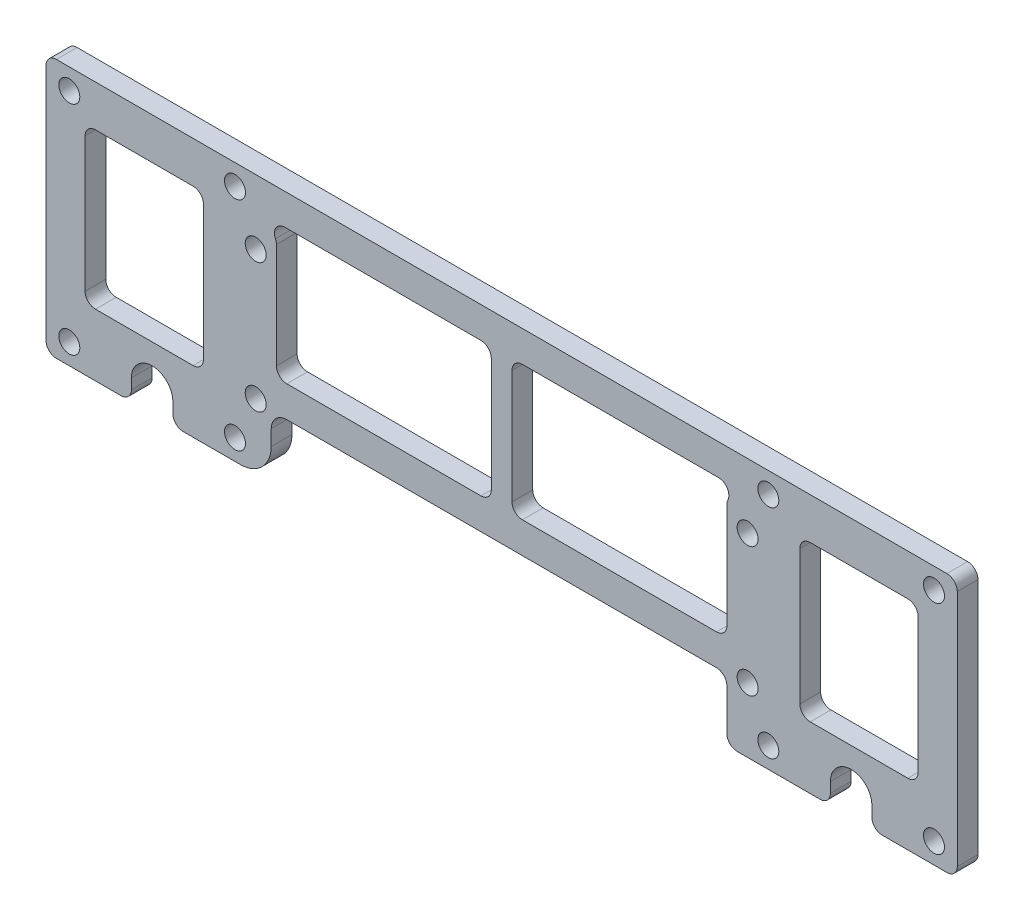
SolidWorks part; units mm, degrees
material "Thornel Mat VMA"
ref_plane "前视基准面" through (0, 0, 0) normal (0, 0, 1) x (1, 0, 0)
ref_plane "上视基准面" through (0, 0, 0) normal (0, 1, 0) x (1, 0, 0)
ref_plane "右视基准面" through (0, 0, 0) normal (1, 0, 0) x (0, 0, -1)
other "Configuration Table"
sketch "草图1" plane through (0, 0, 0) normal (0, 0, 1) x (1, 0, 0)
  line L1 (-88, -25) -> (88, -25)
  line L2 (-88, -25) -> (-88, 25)
  line L3 (-88, 25) -> (88, 25)
  line L4 (88, -25) -> (88, 25)
  line L5 (-88, -25) -> (88, 25) construction
  line L6 (-88, 25) -> (88, -25) construction
  point P0 (0, 0)
  dimension "D1" = 176
  dimension "D2" = 50
extrude "凸台-拉伸1" add sketch "草图1" along normal mid plane 4
sketch "草图2" plane through (0, 0, -2) normal (0, 0, -1) x (-1, 0, 0)
  line L0 (-88, -25) -> (-88, 25) construction
  line L1 (88, -25) -> (-88, -25) construction
  circle A4 centre (51.5, 21) radius 1.65 construction
  circle A5 centre (83.5, 21) radius 1.65 construction
  circle A6 centre (83.5, -21) radius 1.65 construction
  circle A7 centre (51.5, -21) radius 1.65 construction
  circle A8 centre (51.5, 21) radius 2.025
  circle A9 centre (51.5, -21) radius 2.025
  circle A10 centre (83.5, 21) radius 2.025
  circle A11 centre (83.5, -21) radius 2.025
  dimension "D1" = 4.05
  dimension "D2" = 3.3
  dimension "D3" = 139.5
  dimension "D4" = 171.5
  dimension "D5" = 4
  dimension "D6" = 46
extrude "切除-拉伸1" cut sketch "草图2" against normal mid plane 44
mirror "镜向1" about plane through (0, 0, 0) normal (1, 0, 0) of "切除-拉伸1"
sketch "草图3" plane through (0, 0, -2) normal (0, 0, -1) x (-1, 0, 0)
  line L0 (51.5, -21) -> (83.5, -21) construction
  line L1 (88, -25) -> (-88, -25) construction
  line L2 (67.5, -17) -> (64.0359, -19) construction
  line L3 (64.0359, -19) -> (64.0359, -23) construction
  line L4 (64.0359, -23) -> (67.5, -25) construction
  line L5 (67.5, -25) -> (70.9641, -23) construction
  line L6 (70.9641, -23) -> (70.9641, -19) construction
  line L7 (70.9641, -19) -> (67.5, -17) construction
  line L8 (63.5, -21) -> (63.5, -25)
  line L9 (63.5, -25) -> (71.5, -25)
  line L10 (71.5, -25) -> (71.5, -21)
  arc A1 (71.5, -21) -> (63.5, -21) centre (67.5, -21) ccw
extrude "切除-拉伸2" cut sketch "草图3" against normal mid plane 34
mirror "镜向2" about plane through (0, 0, 0) normal (1, 0, 0) of "切除-拉伸2"
fillet "圆角1" radius 2 8 edges at (-63.5, -25, 0) (-71.5, -25, 0) (-88, -25, 0) (-88, 25, 0) (88, 25, 0) (88, -25, 0) (63.5, -25, 0) (71.5, -25, 0)
sketch "草图4" plane through (0, 0, -2) normal (0, 0, -1) x (-1, 0, 0)
  line L0 (0, 0) -> (0, 39.7979) construction
  circle A0 centre (47.5, -12.5) radius 1.65 construction
  circle A1 centre (47.5, 12.5) radius 1.65 construction
  circle A2 centre (47.5, -12.5) radius 1.65 construction
  circle A3 centre (47.5, 12.5) radius 1.65 construction
  circle A4 centre (47.5, -12.5) radius 2.025
  circle A5 centre (47.5, 12.5) radius 2.025
  circle A7 centre (-47.5, 12.5) radius 1.65 construction
  circle A8 centre (-47.5, -12.5) radius 1.65 construction
  circle A9 centre (-47.5, 12.5) radius 2.025
  circle A10 centre (-47.5, -12.5) radius 2.025
  dimension "D1" = 4.05
extrude "切除-拉伸3" cut sketch "草图4" against normal mid plane 10
sketch "草图5" [suppressed] plane through (0, 0, -2) normal (0, 0, -1) x (-1, 0, 0)
  line L0 (61.5, -23) -> (-61.5, -23) construction
  line L1 (-47, -23) -> (47, -23)
  line L2 (-47, -23) -> (-47, -88)
  line L3 (-47, -88) -> (47, -88)
  line L4 (47, -23) -> (47, -88)
  line L5 (0, 0) -> (0, -88) construction
  dimension "D1" = 94
  dimension "D2" = 65
extrude "凸台-拉伸2" [suppressed] add sketch "草图5" against normal up to surface (4 mm away)
sketch "草图7" plane through (0, 0, 2) normal (0, 0, 1) x (1, 0, 0)
  line L5 (-45.0329, 19) -> (-43.5, 15.7427)
  line L6 (-43.5, 15.7427) -> (-43.5, -15.7427)
  line L7 (-43.5, -15.7427) -> (-45.0329, -19)
  line L8 (-45.0329, -19) -> (45.0329, -19)
  line L9 (0, -19) -> (0, 0) construction
  line L10 (-45.0329, 19) -> (45.0329, 19)
  line L11 (0, 0) -> (-43.5, 0) construction
  line L12 (-51.5, 21) -> (-47.5, 12.5) construction
  line L13 (-47.5, 12.5) -> (-47.5, -12.5) construction
  line L14 (-47.5, -12.5) -> (-51.5, -21) construction
  line L15 (-61.5, -25) -> (61.5, -25) construction
  line L16 (45.0329, 19) -> (43.5, 15.7427)
  line L17 (43.5, -15.7427) -> (45.0329, -19)
  line L18 (43.5, 15.7427) -> (43.5, -15.7427)
  line L19 (0, 19) -> (0, -19) construction
  line L20 (-2, 19) -> (-2, -19)
  line L21 (2, 19) -> (2, -19)
  point P23 (0, 19)
  dimension "D1" = 8
  dimension "D2" = 5
  dimension "D3" = 6
  dimension "D4" = 2
  dimension "D5" = 2
extrude "切除-拉伸5" cut sketch "草图7" against normal mid plane 31 contours L20 L10 L5 L6 L7 L8 | L10 L21 L8 L17 L18 L16
sketch "草图8" plane through (0, 0, 2) normal (0, 0, 1) x (1, 0, 0)
  line L0 (-83.5, 21) -> (-51.5, -21) construction
  line L1 (0, 0) -> (0, -25) construction
  line L2 (-80.4524, 17) -> (-57.5952, 17)
  line L3 (-80.4524, 17) -> (-80.4524, -13)
  line L4 (-80.4524, -13) -> (-57.5952, -13)
  line L5 (-57.5952, 17) -> (-57.5952, -13)
  line L6 (-61.5, -25) -> (61.5, -25) construction
  line L7 (80.4524, -13) -> (57.5952, -13)
  line L8 (57.5952, 17) -> (57.5952, -13)
  line L9 (80.4524, 17) -> (57.5952, 17)
  line L10 (80.4524, 17) -> (80.4524, -13)
  circle A0 centre (-51.5, 21) radius 2.025 construction
  arc A1 (-63.5, -21) -> (-71.5, -21) centre (-67.5, -21) ccw construction
  dimension "D1" = 4
  dimension "D2" = 8
extrude "切除-拉伸6" cut sketch "草图8" against normal mid plane 31
fillet "圆角2" radius 2 20 edges at (-45.0329, -19, 0) (-43.5, -15.7427, 0) (-43.5, 15.7427, 0) (-45.0329, 19, 0) (-2, 19, 0) (-2, -19, 0) (43.5, 15.7427, 0) (43.5, -15.7427, 0) (45.0329, -19, 0) (2, -19, 0) (2, 19, 0) (45.0329, 19, 0) (80.4524, -13, 0) (57.5952, -13, 0) (57.5952, 17, 0) (80.4524, 17, 0) (-80.4524, 17, 0) (-57.5952, 17, 0) (-80.4524, -13, 0) (-57.5952, -13, 0)
sketch "草图9" plane through (0, 0, -2) normal (0, 0, -1) x (-1, 0, 0)
  line L0 (0, -52) -> (0, 0) construction
  line L1 (65, -79) -> (-65, -79)
  line L2 (65, -79) -> (65, -25)
  line L3 (65, -25) -> (-65, -25)
  line L4 (-65, -79) -> (-65, -25)
  line L5 (65, -79) -> (-65, -25) construction
  line L6 (65, -25) -> (-65, -79) construction
  line L8 (61.5, -25) -> (-61.5, -25) construction
  point P0 (0, -52)
  dimension "D1" = 54
  dimension "D2" = 130
extrude "凸台-拉伸3" [suppressed] add sketch "草图9" against normal up to surface (4 mm away)
sketch "草图10" [suppressed] plane through (0, 0, -2) normal (0, 0, -1) x (-1, 0, 0)
  line L0 (-65, -79) -> (65, -79) construction
  line L1 (54.75, -26) -> (-54.75, -26)
  line L2 (54.75, -26) -> (54.75, -79)
  line L3 (54.75, -79) -> (-54.75, -79)
  line L4 (-54.75, -26) -> (-54.75, -79)
  line L5 (54.75, -26) -> (-54.75, -79) construction
  line L6 (54.75, -79) -> (-54.75, -26) construction
  line L7 (0, -52.5) -> (0, 0) construction
  point P0 (0, -52.5)
  dimension "D1" = 109.5
  dimension "D2" = 53
extrude "切除-拉伸7" [suppressed] cut sketch "草图10" against normal blind 10
sketch "草图11" [suppressed] plane through (0, 0, -2) normal (0, 0, -1) x (-1, 0, 0)
  line L1 (51.75, -26) -> (-51.75, -26)
  line L2 (51.75, -26) -> (51.75, -79)
  line L3 (51.75, -79) -> (-51.75, -79)
  line L4 (54.75, -26) -> (-54.75, -26)
  line L5 (-54.75, -26) -> (-54.75, -79)
  line L6 (-54.75, -79) -> (54.75, -79)
  line L7 (54.75, -79) -> (54.75, -26)
  line L8 (54.75, -26) -> (-54.75, -26)
  line L9 (-54.75, -26) -> (-54.75, -79)
  line L10 (-54.75, -79) -> (54.75, -79)
  line L11 (54.75, -79) -> (54.75, -26)
  line L12 (-51.75, -26) -> (-51.75, -79)
  line L13 (44.75, -26) -> (-44.75, -26)
  line L14 (44.75, -26) -> (44.75, -79)
  line L15 (44.75, -79) -> (-44.75, -79)
  line L16 (-44.75, -26) -> (-44.75, -79)
  dimension "D2" = 3
  dimension "D3" = 3
  dimension "D4" = 7
  dimension "D5" = 7
  dimension "D1" = 0
extrude "凸台-拉伸4" [suppressed] add sketch "草图11" against normal up to surface (4 mm away) contours L1 L14 L3 L2 | L16 L1 L12 L3
sketch "草图12" plane through (0, 0, -2) normal (0, 0, -1) x (-1, 0, 0)
  line L0 (-65, -25) -> (65, -25)
  line L2 (-51.75, -26) -> (-51.75, -25)
  line L3 (51.75, -26) -> (51.75, -25)
  line L13 (-61.5, -25) -> (61.5, -25)
  line L14 (-61.5, -25) -> (61.5, -25)
  line L44 (63.5, -23) -> (63.5, -21)
  line L45 (71.5, -21) -> (71.5, -23)
  line L46 (73.5, -25) -> (86, -25)
  line L47 (88, -23) -> (88, 23)
  line L48 (86, 25) -> (-86, 25)
  line L49 (-88, 23) -> (-88, -23)
  line L50 (-86, -25) -> (-73.5, -25)
  line L51 (-71.5, -23) -> (-71.5, -21)
  line L52 (-63.5, -21) -> (-63.5, -23)
  line L70 (63.5, -23) -> (63.5, -21)
  line L71 (71.5, -21) -> (71.5, -23)
  line L72 (73.5, -25) -> (86, -25)
  line L73 (88, -23) -> (88, 23)
  line L74 (86, 25) -> (-86, 25)
  line L75 (-88, 23) -> (-88, -23)
  line L76 (-86, -25) -> (-73.5, -25)
  line L77 (-71.5, -23) -> (-71.5, -21)
  line L78 (-63.5, -21) -> (-63.5, -23)
  arc A10 (61.5, -25) -> (63.5, -23) centre (61.5, -23) ccw
  arc A11 (71.5, -21) -> (63.5, -21) centre (67.5, -21) ccw
  arc A12 (71.5, -23) -> (73.5, -25) centre (73.5, -23) ccw
  arc A13 (86, -25) -> (88, -23) centre (86, -23) ccw
  arc A14 (88, 23) -> (86, 25) centre (86, 23) ccw
  arc A15 (-86, 25) -> (-88, 23) centre (-86, 23) ccw
  arc A16 (-88, -23) -> (-86, -25) centre (-86, -23) ccw
  arc A17 (-73.5, -25) -> (-71.5, -23) centre (-73.5, -23) ccw
  arc A18 (-63.5, -21) -> (-71.5, -21) centre (-67.5, -21) ccw
  arc A19 (-63.5, -23) -> (-61.5, -25) centre (-61.5, -23) ccw
  arc A20 (61.5, -25) -> (63.5, -23) centre (61.5, -23) ccw
  arc A21 (71.5, -21) -> (63.5, -21) centre (67.5, -21) ccw
  arc A22 (71.5, -23) -> (73.5, -25) centre (73.5, -23) ccw
  arc A23 (86, -25) -> (88, -23) centre (86, -23) ccw
  arc A24 (88, 23) -> (86, 25) centre (86, 23) ccw
  arc A25 (-86, 25) -> (-88, 23) centre (-86, 23) ccw
  arc A26 (-88, -23) -> (-86, -25) centre (-86, -23) ccw
  arc A27 (-73.5, -25) -> (-71.5, -23) centre (-73.5, -23) ccw
  arc A28 (-63.5, -21) -> (-71.5, -21) centre (-67.5, -21) ccw
  arc A29 (-63.5, -23) -> (-61.5, -25) centre (-61.5, -23) ccw
  dimension "D1" = 0
extrude "切除-拉伸8" [suppressed] cut sketch "草图12" against normal blind 10
sketch "草图13" plane through (0, 0, 2) normal (0, 0, 1) x (1, 0, 0)
  line L0 (0, -54) -> (0, 0) construction
  line L1 (-48.75, -44) -> (48.75, -44) construction
  line L2 (-48.75, -44) -> (-48.75, -64) construction
  line L3 (-48.75, -64) -> (48.75, -64) construction
  line L4 (48.75, -44) -> (48.75, -64) construction
  line L5 (-48.75, -44) -> (48.75, -64) construction
  line L6 (-48.75, -64) -> (48.75, -44) construction
  circle A2 centre (-48.75, -44) radius 1.51
  circle A3 centre (-48.75, -64) radius 1.51
  circle A4 centre (48.75, -44) radius 1.51
  circle A5 centre (48.75, -64) radius 1.51
  point P0 (0, -54)
  dimension "D4" = 3.02
  dimension "D1" = 97.5
  dimension "D2" = 20
  dimension "D3" = 44
extrude "切除-拉伸9" [suppressed] cut sketch "草图13" against normal blind 10
fillet "圆角3" [suppressed] radius 15
sketch "草图14" [suppressed] plane through (0, 0, -2) normal (0, 0, -1) x (-1, 0, 0)
  line L4 (-80.4524, 15) -> (-80.4524, -11)
  line L5 (-59.5952, 17) -> (-78.4524, 17)
  line L6 (-43.5, 15.2956) -> (-43.5, -15.2956)
  line L7 (-43.6909, 16.1484) -> (-43.6904, 16.1472)
  line L8 (-4, 19) -> (-41.8813, 19)
  line L9 (-2, -17) -> (-2, 17)
  line L10 (-41.8813, -19) -> (-4, -19)
  line L11 (-43.6904, -16.1472) -> (-43.6909, -16.1484)
  line L12 (-43.5, 15.2956) -> (-43.5, -15.2956)
  line L13 (-43.6909, 16.1484) -> (-43.6904, 16.1472)
  line L14 (-4, 19) -> (-41.8813, 19)
  line L15 (-2, -17) -> (-2, 17)
  line L16 (-41.8813, -19) -> (-4, -19)
  line L17 (-43.6904, -16.1472) -> (-43.6909, -16.1484)
  line L18 (43.5, -15.2956) -> (43.5, 15.2956)
  line L19 (43.6909, -16.1484) -> (43.6904, -16.1472)
  line L20 (4, -19) -> (41.8813, -19)
  line L21 (2, 17) -> (2, -17)
  line L22 (41.8813, 19) -> (4, 19)
  line L23 (43.6904, 16.1472) -> (43.6909, 16.1484)
  line L24 (43.5, -15.2956) -> (43.5, 15.2956)
  line L25 (43.6909, -16.1484) -> (43.6904, -16.1472)
  line L26 (4, -19) -> (41.8813, -19)
  line L27 (2, 17) -> (2, -17)
  line L28 (41.8813, 19) -> (4, 19)
  line L29 (43.6904, 16.1472) -> (43.6909, 16.1484)
  line L30 (-57.5952, -11) -> (-57.5952, 15)
  line L31 (-78.4524, -13) -> (-59.5952, -13)
  line L32 (-80.4524, 15) -> (-80.4524, -11)
  line L33 (-59.5952, 17) -> (-78.4524, 17)
  line L34 (-57.5952, -11) -> (-57.5952, 15)
  line L35 (-78.4524, -13) -> (-59.5952, -13)
  line L36 (80.4524, -11) -> (80.4524, 15)
  line L37 (59.5952, -13) -> (78.4524, -13)
  line L38 (57.5952, 15) -> (57.5952, -11)
  line L39 (78.4524, 17) -> (59.5952, 17)
  line L40 (80.4524, -11) -> (80.4524, 15)
  line L41 (59.5952, -13) -> (78.4524, -13)
  line L42 (57.5952, 15) -> (57.5952, -11)
  line L43 (78.4524, 17) -> (59.5952, 17)
  circle A1 centre (51.5, 21) radius 2.025
  circle A2 centre (51.5, 21) radius 2.025
  circle A3 centre (83.5, -21) radius 2.025
  circle A4 centre (83.5, -21) radius 2.025
  circle A5 centre (83.5, 21) radius 2.025
  circle A6 centre (83.5, 21) radius 2.025
  circle A7 centre (51.5, -21) radius 2.025
  circle A8 centre (51.5, -21) radius 2.025
  circle A9 centre (-51.5, 21) radius 2.025
  circle A10 centre (-51.5, 21) radius 2.025
  circle A11 centre (-83.5, -21) radius 2.025
  circle A12 centre (-83.5, -21) radius 2.025
  circle A13 centre (-83.5, 21) radius 2.025
  circle A14 centre (-83.5, 21) radius 2.025
  circle A15 centre (-51.5, -21) radius 2.025
  circle A16 centre (-51.5, -21) radius 2.025
  circle A17 centre (47.5, -12.5) radius 2.025
  circle A18 centre (47.5, -12.5) radius 2.025
  circle A19 centre (47.5, 12.5) radius 2.025
  circle A20 centre (47.5, 12.5) radius 2.025
  circle A21 centre (-47.5, 12.5) radius 2.025
  circle A22 centre (-47.5, 12.5) radius 2.025
  circle A23 centre (-47.5, -12.5) radius 2.025
  circle A24 centre (-47.5, -12.5) radius 2.025
  circle A25 centre (48.75, -44) radius 1.51
  circle A26 centre (48.75, -44) radius 1.51
  circle A27 centre (-48.75, -64) radius 1.51
  arc A28 (-78.4524, 17) -> (-80.4524, 15) centre (-78.4524, 15) ccw
  arc A29 (-57.5952, 15) -> (-59.5952, 17) centre (-59.5952, 15) ccw
  arc A30 (-43.5, 15.2956) -> (-43.6904, 16.1472) centre (-45.5, 15.2956) ccw
  arc A31 (-41.8813, 19) -> (-43.6909, 16.1484) centre (-41.8813, 17) ccw
  arc A32 (-2, 17) -> (-4, 19) centre (-4, 17) ccw
  arc A33 (-4, -19) -> (-2, -17) centre (-4, -17) ccw
  arc A34 (-43.6909, -16.1484) -> (-41.8813, -19) centre (-41.8813, -17) ccw
  arc A35 (-43.6904, -16.1472) -> (-43.5, -15.2956) centre (-45.5, -15.2956) ccw
  arc A36 (-43.5, 15.2956) -> (-43.6904, 16.1472) centre (-45.5, 15.2956) ccw
  arc A37 (-41.8813, 19) -> (-43.6909, 16.1484) centre (-41.8813, 17) ccw
  arc A38 (-2, 17) -> (-4, 19) centre (-4, 17) ccw
  arc A39 (-4, -19) -> (-2, -17) centre (-4, -17) ccw
  arc A40 (-43.6909, -16.1484) -> (-41.8813, -19) centre (-41.8813, -17) ccw
  arc A41 (-43.6904, -16.1472) -> (-43.5, -15.2956) centre (-45.5, -15.2956) ccw
  arc A42 (43.5, -15.2956) -> (43.6904, -16.1472) centre (45.5, -15.2956) ccw
  arc A43 (41.8813, -19) -> (43.6909, -16.1484) centre (41.8813, -17) ccw
  arc A44 (2, -17) -> (4, -19) centre (4, -17) ccw
  arc A45 (4, 19) -> (2, 17) centre (4, 17) ccw
  arc A46 (43.6909, 16.1484) -> (41.8813, 19) centre (41.8813, 17) ccw
  arc A47 (43.6904, 16.1472) -> (43.5, 15.2956) centre (45.5, 15.2956) ccw
  arc A48 (43.5, -15.2956) -> (43.6904, -16.1472) centre (45.5, -15.2956) ccw
  arc A49 (41.8813, -19) -> (43.6909, -16.1484) centre (41.8813, -17) ccw
  arc A50 (2, -17) -> (4, -19) centre (4, -17) ccw
  arc A51 (4, 19) -> (2, 17) centre (4, 17) ccw
  arc A52 (43.6909, 16.1484) -> (41.8813, 19) centre (41.8813, 17) ccw
  arc A53 (43.6904, 16.1472) -> (43.5, 15.2956) centre (45.5, 15.2956) ccw
  arc A54 (-59.5952, -13) -> (-57.5952, -11) centre (-59.5952, -11) ccw
  arc A55 (-80.4524, -11) -> (-78.4524, -13) centre (-78.4524, -11) ccw
  arc A56 (-78.4524, 17) -> (-80.4524, 15) centre (-78.4524, 15) ccw
  arc A57 (-57.5952, 15) -> (-59.5952, 17) centre (-59.5952, 15) ccw
  arc A58 (-59.5952, -13) -> (-57.5952, -11) centre (-59.5952, -11) ccw
  arc A59 (-80.4524, -11) -> (-78.4524, -13) centre (-78.4524, -11) ccw
  arc A60 (78.4524, -13) -> (80.4524, -11) centre (78.4524, -11) ccw
  arc A61 (57.5952, -11) -> (59.5952, -13) centre (59.5952, -11) ccw
  arc A62 (59.5952, 17) -> (57.5952, 15) centre (59.5952, 15) ccw
  arc A63 (80.4524, 15) -> (78.4524, 17) centre (78.4524, 15) ccw
  arc A64 (78.4524, -13) -> (80.4524, -11) centre (78.4524, -11) ccw
  arc A65 (57.5952, -11) -> (59.5952, -13) centre (59.5952, -11) ccw
  arc A66 (59.5952, 17) -> (57.5952, 15) centre (59.5952, 15) ccw
  arc A67 (80.4524, 15) -> (78.4524, 17) centre (78.4524, 15) ccw
  circle A68 centre (-48.75, -64) radius 1.51
  circle A69 centre (-48.75, -44) radius 1.51
  circle A70 centre (-48.75, -44) radius 1.51
  circle A71 centre (48.75, -64) radius 1.51
  circle A72 centre (48.75, -64) radius 1.51
  dimension "D1" = 0
  dimension "D2" = 0
  dimension "D3" = 0
  dimension "D4" = 0
  dimension "D5" = 0
  dimension "D6" = 0
  dimension "D7" = 0
  dimension "D8" = 0
  dimension "D9" = 0
  dimension "D10" = 0
  dimension "D11" = 0
  dimension "D12" = 0
  dimension "D13" = 0
  dimension "D14" = 0
  dimension "D15" = 0
  dimension "D16" = 0
  dimension "D17" = 0
  dimension "D18" = 0
  dimension "D19" = 0
  dimension "D20" = 0
other "移动面2" [suppressed] parameters "D1"=1
sketch "草图15" [suppressed] plane through (0, 0, -2) normal (0, 0, -1) x (-1, 0, 0)
  line L0 (45.75, -26) -> (43.8413, -16.6019)
  line L1 (-44.75, -26) -> (-43.8722, -16.8098)
  line L2 (-44.75, -26) -> (45.75, -26)
  line L3 (4, 19) -> (-4, 19)
  line L4 (-80.4524, 15) -> (-80.4524, -11)
  line L5 (-59.5952, 17) -> (-78.4524, 17)
  line L6 (-43.5, 15.2956) -> (-43.5, -15.2956)
  line L7 (-43.6909, 16.1484) -> (-43.6904, 16.1472)
  line L8 (-4, 19) -> (-41.8813, 19)
  line L9 (-2, -17) -> (-2, 17)
  line L10 (-41.8813, -19) -> (-4, -19)
  line L11 (-43.6904, -16.1472) -> (-43.6909, -16.1484)
  line L12 (-43.5, 15.2956) -> (-43.5, -15.2956)
  line L13 (-43.6909, 16.1484) -> (-43.6904, 16.1472)
  line L14 (-4, 19) -> (-41.8813, 19)
  line L15 (-2, -17) -> (-2, 17)
  line L16 (-41.8813, -19) -> (-4, -19)
  line L17 (-43.6904, -16.1472) -> (-43.6909, -16.1484)
  line L18 (43.5, -15.2956) -> (43.5, 15.2956)
  line L19 (43.6909, -16.1484) -> (43.6904, -16.1472)
  line L20 (4, -19) -> (41.8813, -19)
  line L21 (2, 17) -> (2, -17)
  line L22 (41.8813, 19) -> (4, 19)
  line L23 (43.6904, 16.1472) -> (43.6909, 16.1484)
  line L24 (43.5, -15.2956) -> (43.5, 15.2956)
  line L25 (43.6909, -16.1484) -> (43.6904, -16.1472)
  line L26 (4, -19) -> (41.8813, -19)
  line L27 (2, 17) -> (2, -17)
  line L28 (41.8813, 19) -> (4, 19)
  line L29 (43.6904, 16.1472) -> (43.6909, 16.1484)
  line L30 (-57.5952, -11) -> (-57.5952, 15)
  line L31 (-78.4524, -13) -> (-59.5952, -13)
  line L32 (-80.4524, 15) -> (-80.4524, -11)
  line L33 (-59.5952, 17) -> (-78.4524, 17)
  line L34 (-57.5952, -11) -> (-57.5952, 15)
  line L35 (-78.4524, -13) -> (-59.5952, -13)
  line L36 (80.4524, -11) -> (80.4524, 15)
  line L37 (59.5952, -13) -> (78.4524, -13)
  line L38 (57.5952, 15) -> (57.5952, -11)
  line L39 (78.4524, 17) -> (59.5952, 17)
  line L40 (80.4524, -11) -> (80.4524, 15)
  line L41 (59.5952, -13) -> (78.4524, -13)
  line L42 (57.5952, 15) -> (57.5952, -11)
  line L43 (78.4524, 17) -> (59.5952, 17)
  line L44 (-44.75, -79) -> (-40.75, -79)
  line L45 (-40.75, -79) -> (-40.75, -39)
  line L46 (-40.75, -39) -> (-20.75, -26)
  line L60 (51.75, -79) -> (51.75, -25)
  line L61 (63.5, -23) -> (63.5, -21)
  line L62 (71.5, -21) -> (71.5, -23)
  line L63 (73.5, -25) -> (86, -25)
  line L64 (88, -23) -> (88, 23)
  line L65 (86, 25) -> (-86, 25)
  line L66 (-88, 23) -> (-88, -23)
  line L67 (-86, -25) -> (-73.5, -25)
  line L68 (-71.5, -23) -> (-71.5, -21)
  line L69 (-63.5, -21) -> (-63.5, -23)
  line L70 (-51.75, -25) -> (-51.75, -79)
  line L71 (-51.75, -79) -> (-44.75, -79)
  line L72 (-44.75, -79) -> (-44.75, -26)
  line L73 (-44.75, -26) -> (44.75, -26)
  line L74 (44.75, -26) -> (44.75, -79)
  line L75 (44.75, -79) -> (51.75, -79)
  line L76 (51.75, -79) -> (51.75, -25)
  line L77 (63.5, -23) -> (63.5, -21)
  line L78 (71.5, -21) -> (71.5, -23)
  line L79 (73.5, -25) -> (86, -25)
  line L80 (88, -23) -> (88, 23)
  line L81 (86, 25) -> (-86, 25)
  line L82 (-88, 23) -> (-88, -23)
  line L83 (-86, -25) -> (-73.5, -25)
  line L84 (-71.5, -23) -> (-71.5, -21)
  line L85 (-63.5, -21) -> (-63.5, -23)
  line L86 (-51.75, -25) -> (-51.75, -79)
  line L87 (-51.75, -79) -> (-44.75, -79)
  line L88 (-44.75, -79) -> (-44.75, -26)
  line L89 (-44.75, -26) -> (44.75, -26)
  line L90 (44.75, -26) -> (44.75, -79)
  line L91 (44.75, -79) -> (51.75, -79)
  line L97 (51.75, -25) -> (61.5, -25)
  line L98 (51.75, -25) -> (61.5, -25)
  line L99 (-61.5, -25) -> (-51.75, -25)
  line L100 (-61.5, -25) -> (-51.75, -25)
  arc A0 (41.8813, -19) -> (43.6909, -16.1484) centre (41.8813, -17) ccw construction
  circle A1 centre (51.5, 21) radius 2.025
  circle A2 centre (51.5, 21) radius 2.025
  circle A3 centre (83.5, -21) radius 2.025
  circle A4 centre (83.5, -21) radius 2.025
  circle A5 centre (83.5, 21) radius 2.025
  circle A6 centre (83.5, 21) radius 2.025
  circle A7 centre (51.5, -21) radius 2.025
  circle A8 centre (51.5, -21) radius 2.025
  circle A9 centre (-51.5, 21) radius 2.025
  circle A10 centre (-51.5, 21) radius 2.025
  circle A11 centre (-83.5, -21) radius 2.025
  circle A12 centre (-83.5, -21) radius 2.025
  circle A13 centre (-83.5, 21) radius 2.025
  circle A14 centre (-83.5, 21) radius 2.025
  circle A15 centre (-51.5, -21) radius 2.025
  circle A16 centre (-51.5, -21) radius 2.025
  circle A17 centre (47.5, -12.5) radius 2.025
  circle A18 centre (47.5, -12.5) radius 2.025
  circle A19 centre (47.5, 12.5) radius 2.025
  circle A20 centre (47.5, 12.5) radius 2.025
  circle A21 centre (-47.5, 12.5) radius 2.025
  circle A22 centre (-47.5, 12.5) radius 2.025
  circle A23 centre (-47.5, -12.5) radius 2.025
  circle A24 centre (-47.5, -12.5) radius 2.025
  circle A25 centre (48.75, -44) radius 1.51
  circle A26 centre (48.75, -44) radius 1.51
  circle A27 centre (-48.75, -64) radius 1.51
  arc A28 (-78.4524, 17) -> (-80.4524, 15) centre (-78.4524, 15) ccw
  arc A29 (-57.5952, 15) -> (-59.5952, 17) centre (-59.5952, 15) ccw
  arc A30 (-43.5, 15.2956) -> (-43.6904, 16.1472) centre (-45.5, 15.2956) ccw
  arc A31 (-41.8813, 19) -> (-43.6909, 16.1484) centre (-41.8813, 17) ccw
  arc A32 (-2, 17) -> (-4, 19) centre (-4, 17) ccw
  arc A33 (-4, -19) -> (-2, -17) centre (-4, -17) ccw
  arc A34 (-43.6909, -16.1484) -> (-41.8813, -19) centre (-41.8813, -17) ccw
  arc A35 (-43.6904, -16.1472) -> (-43.5, -15.2956) centre (-45.5, -15.2956) ccw
  arc A36 (-43.5, 15.2956) -> (-43.6904, 16.1472) centre (-45.5, 15.2956) ccw
  arc A37 (-41.8813, 19) -> (-43.6909, 16.1484) centre (-41.8813, 17) ccw
  arc A38 (-2, 17) -> (-4, 19) centre (-4, 17) ccw
  arc A39 (-4, -19) -> (-2, -17) centre (-4, -17) ccw
  arc A40 (-43.6909, -16.1484) -> (-41.8813, -19) centre (-41.8813, -17) ccw
  arc A41 (-43.6904, -16.1472) -> (-43.5, -15.2956) centre (-45.5, -15.2956) ccw
  arc A42 (43.5, -15.2956) -> (43.6904, -16.1472) centre (45.5, -15.2956) ccw
  arc A43 (41.8813, -19) -> (43.6909, -16.1484) centre (41.8813, -17) ccw
  arc A44 (2, -17) -> (4, -19) centre (4, -17) ccw
  arc A45 (4, 19) -> (2, 17) centre (4, 17) ccw
  arc A46 (43.6909, 16.1484) -> (41.8813, 19) centre (41.8813, 17) ccw
  arc A47 (43.6904, 16.1472) -> (43.5, 15.2956) centre (45.5, 15.2956) ccw
  arc A48 (43.5, -15.2956) -> (43.6904, -16.1472) centre (45.5, -15.2956) ccw
  arc A49 (41.8813, -19) -> (43.6909, -16.1484) centre (41.8813, -17) ccw
  arc A50 (2, -17) -> (4, -19) centre (4, -17) ccw
  arc A51 (4, 19) -> (2, 17) centre (4, 17) ccw
  arc A52 (43.6909, 16.1484) -> (41.8813, 19) centre (41.8813, 17) ccw
  arc A53 (43.6904, 16.1472) -> (43.5, 15.2956) centre (45.5, 15.2956) ccw
  arc A54 (-59.5952, -13) -> (-57.5952, -11) centre (-59.5952, -11) ccw
  arc A55 (-80.4524, -11) -> (-78.4524, -13) centre (-78.4524, -11) ccw
  arc A56 (-78.4524, 17) -> (-80.4524, 15) centre (-78.4524, 15) ccw
  arc A57 (-57.5952, 15) -> (-59.5952, 17) centre (-59.5952, 15) ccw
  arc A58 (-59.5952, -13) -> (-57.5952, -11) centre (-59.5952, -11) ccw
  arc A59 (-80.4524, -11) -> (-78.4524, -13) centre (-78.4524, -11) ccw
  arc A60 (78.4524, -13) -> (80.4524, -11) centre (78.4524, -11) ccw
  arc A61 (57.5952, -11) -> (59.5952, -13) centre (59.5952, -11) ccw
  arc A62 (59.5952, 17) -> (57.5952, 15) centre (59.5952, 15) ccw
  arc A63 (80.4524, 15) -> (78.4524, 17) centre (78.4524, 15) ccw
  arc A64 (78.4524, -13) -> (80.4524, -11) centre (78.4524, -11) ccw
  arc A65 (57.5952, -11) -> (59.5952, -13) centre (59.5952, -11) ccw
  arc A66 (59.5952, 17) -> (57.5952, 15) centre (59.5952, 15) ccw
  arc A67 (80.4524, 15) -> (78.4524, 17) centre (78.4524, 15) ccw
  circle A68 centre (-48.75, -64) radius 1.51
  circle A69 centre (-48.75, -44) radius 1.51
  circle A70 centre (-48.75, -44) radius 1.51
  circle A71 centre (48.75, -64) radius 1.51
  circle A72 centre (48.75, -64) radius 1.51
  arc A87 (61.5, -25) -> (63.5, -23) centre (61.5, -23) ccw
  arc A88 (71.5, -21) -> (63.5, -21) centre (67.5, -21) ccw
  arc A89 (71.5, -23) -> (73.5, -25) centre (73.5, -23) ccw
  arc A90 (86, -25) -> (88, -23) centre (86, -23) ccw
  arc A91 (88, 23) -> (86, 25) centre (86, 23) ccw
  arc A92 (-86, 25) -> (-88, 23) centre (-86, 23) ccw
  arc A93 (-88, -23) -> (-86, -25) centre (-86, -23) ccw
  arc A94 (-73.5, -25) -> (-71.5, -23) centre (-73.5, -23) ccw
  arc A95 (-63.5, -21) -> (-71.5, -21) centre (-67.5, -21) ccw
  arc A96 (-63.5, -23) -> (-61.5, -25) centre (-61.5, -23) ccw
  arc A99 (61.5, -25) -> (63.5, -23) centre (61.5, -23) ccw
  arc A100 (71.5, -21) -> (63.5, -21) centre (67.5, -21) ccw
  arc A101 (71.5, -23) -> (73.5, -25) centre (73.5, -23) ccw
  arc A102 (86, -25) -> (88, -23) centre (86, -23) ccw
  arc A103 (88, 23) -> (86, 25) centre (86, 23) ccw
  arc A104 (-86, 25) -> (-88, 23) centre (-86, 23) ccw
  arc A105 (-88, -23) -> (-86, -25) centre (-86, -23) ccw
  arc A106 (-73.5, -25) -> (-71.5, -23) centre (-73.5, -23) ccw
  arc A107 (-63.5, -21) -> (-71.5, -21) centre (-67.5, -21) ccw
  arc A108 (-63.5, -23) -> (-61.5, -25) centre (-61.5, -23) ccw
  dimension "D22" = 4
  dimension "D23" = 13
  dimension "D24" = 20
  dimension "D1" = 0
  dimension "D2" = 0
  dimension "D3" = 0
  dimension "D4" = 0
  dimension "D5" = 0
  dimension "D6" = 0
  dimension "D7" = 0
  dimension "D8" = 0
  dimension "D9" = 0
  dimension "D10" = 0
  dimension "D11" = 0
  dimension "D12" = 0
  dimension "D13" = 0
  dimension "D14" = 0
  dimension "D15" = 0
  dimension "D16" = 0
  dimension "D17" = 0
  dimension "D18" = 0
  dimension "D19" = 0
  dimension "D20" = 0
  dimension "D21" = 0
extrude "凸台-拉伸5" [suppressed] add sketch "草图15" against normal up to surface (4 mm away) contours L88 L44 L45 L46 L2
sketch "草图16" [suppressed] plane through (0, 0, 2) normal (0, 0, 1) x (1, 0, 0)
  line L0 (-20.75, -26) -> (-8.75, -14)
  line L1 (-8.75, -14) -> (8.75, -14)
  line L2 (8.75, -14) -> (20.75, -26)
  line L3 (20.75, -26) -> (40.75, -39) construction
  line L4 (-45.75, -26) -> (20.75, -26) construction
  line L5 (0, 0) -> (0, -22.2739) construction
  line L6 (-20.75, -26) -> (20.75, -26)
  dimension "D1" = 45
  dimension "D2" = 14
extrude "切除-拉伸11" [suppressed] cut sketch "草图16" against normal blind 10
sketch "草图17" [suppressed] plane through (0, 0, -2) normal (0, 0, -1) x (-1, 0, 0)
  line L0 (30.4069, -30) -> (10.4069, -10)
  line L1 (10.4069, -10) -> (-10.4069, -10)
  line L2 (-10.4069, -10) -> (-30.4069, -30)
  line L3 (-30.4069, -30) -> (30.4069, -30)
  line L4 (20.75, -26) -> (8.75, -14)
  line L5 (8.75, -14) -> (-8.75, -14)
  line L6 (-8.75, -14) -> (-20.75, -26)
  line L7 (-20.75, -26) -> (20.75, -26)
  line L8 (20.75, -26) -> (8.75, -14)
  line L9 (8.75, -14) -> (-8.75, -14)
  line L10 (-8.75, -14) -> (-20.75, -26)
  line L11 (-20.75, -26) -> (20.75, -26)
  line L12 (-17, -16.5931) -> (-17, 19)
  line L13 (-41.8813, 19) -> (-4, 19) construction
  line L14 (45.75, -37) -> (30.4069, -30)
  line L15 (26.4069, -26) -> (45.75, -26)
  line L16 (45.75, -26) -> (45.75, -37)
  line L17 (45.75, -26) -> (45.75, -79) construction
  line L18 (17, -16.5931) -> (17, 19)
  line L19 (4, 19) -> (41.8813, 19) construction
  line L20 (17, -4) -> (32, -19)
  line L21 (13.75, -19) -> (41.8813, -19) construction
  line L22 (19.4069, -19) -> (32, -19)
  line L23 (-13.75, -19) -> (-19.4069, -19)
  line L24 (19.4069, -19) -> (13.75, -19)
  line L25 (-17, 19) -> (17, 19)
  line L26 (-17, -4) -> (-32, -19)
  line L27 (-32, -19) -> (-19.4069, -19)
  dimension "D3" = 11
  dimension "D4" = 45
  dimension "D5" = 32
  dimension "D6" = 17
  dimension "D7" = 17
  dimension "D8" = 45
  dimension "D1" = 0
  dimension "D2" = 4
extrude "凸台-拉伸6" [suppressed] add sketch "草图17" against normal up to surface (4 mm away) contours L24 L0 L1 L2 L23 L10 L9 L8 | L25 L12 L2 L1 L0 L18 | L0 L22 L20 L18 | L16 L15 L0 L14 | L26 L27 L2 L12
fillet "圆角4" [suppressed] radius 15
fillet "圆角5" [suppressed] radius 7
sketch "草图18" [suppressed] plane through (0, 0, 2) normal (0, 0, 1) x (1, 0, 0)
  line L0 (-30.4069, -30) -> (-20.0038, -25.2538)
  line L1 (-20.0038, -25.2538) -> (-20.75, -26)
  line L2 (-20.75, -26) -> (-26.4069, -26)
  line L3 (-26.4069, -26) -> (-30.4069, -30)
  line L7 (-8.75, -14) -> (-20.75, -26) construction
  line L8 (-30.4069, -30) -> (-41.6555, -35.132) construction
extrude "凸台-拉伸7" [suppressed] add sketch "草图18" against normal up to surface (4 mm away) contours L2 L3 L0
sketch "草图19" [suppressed] plane through (0, 0, 2) normal (0, 0, 1) x (1, 0, 0)
  line L0 (-21.6393, -26) -> (-20.75, -26)
  line L1 (-20.75, -26) -> (-20.0038, -25.2538)
  line L2 (-20.0038, -25.2538) -> (-21.6393, -26)
  line L3 (-30.4069, -30) -> (-41.6555, -35.132) construction
  line L4 (-8.75, -14) -> (-20.75, -26) construction
extrude "切除-拉伸12" [suppressed] cut sketch "草图19" against normal blind 10 contours L2 L0 L1
fillet "圆角6" [suppressed] radius 20
fillet "圆角7" [suppressed] radius 8
sketch "草图21" [suppressed] plane through (0, 0, 2) normal (0, 0, 1) x (1, 0, 0)
  line L0 (-51.75, -67) -> (51.75, -67)
  line L1 (51.75, -79) -> (51.75, -26) construction
  line L18 (44.75, -26) -> (44.75, -79)
  line L19 (44.75, -26) -> (44.75, -79)
  line L22 (-54.75, -26) -> (-51.75, -26)
  line L23 (44.75, -79) -> (51.75, -79)
  line L24 (51.75, -79) -> (51.75, -26)
  line L25 (63.5, -23) -> (63.5, -21)
  line L26 (71.5, -21) -> (71.5, -23)
  line L27 (73.5, -25) -> (86, -25)
  line L28 (88, -23) -> (88, 23)
  line L29 (86, 25) -> (-86, 25)
  line L30 (-88, 23) -> (-88, -23)
  line L31 (-86, -25) -> (-73.5, -25)
  line L32 (-71.5, -23) -> (-71.5, -21)
  line L33 (-63.5, -21) -> (-63.5, -23)
  line L34 (-51.75, -26) -> (-51.75, -79)
  line L35 (-51.75, -79) -> (-44.75, -79)
  line L36 (-44.75, -79) -> (-44.75, -26)
  line L43 (44.75, -79) -> (51.75, -79)
  line L44 (51.75, -79) -> (51.75, -26)
  line L45 (63.5, -23) -> (63.5, -21)
  line L46 (71.5, -21) -> (71.5, -23)
  line L47 (73.5, -25) -> (86, -25)
  line L48 (88, -23) -> (88, 23)
  line L49 (86, 25) -> (-86, 25)
  line L50 (-88, 23) -> (-88, -23)
  line L51 (-86, -25) -> (-73.5, -25)
  line L52 (-71.5, -23) -> (-71.5, -21)
  line L53 (-63.5, -21) -> (-63.5, -23)
  line L54 (-51.75, -26) -> (-51.75, -79)
  line L55 (-51.75, -79) -> (-44.75, -79)
  line L56 (-44.75, -79) -> (-44.75, -26)
  line L60 (-54.75, -26) -> (-51.75, -26)
  line L67 (-44.75, -26) -> (44.75, -26)
  line L74 (-44.75, -26) -> (44.75, -26)
  line L75 (51.75, -26) -> (54.75, -26)
  line L76 (51.75, -26) -> (54.75, -26)
  line L77 (54.75, -26) -> (54.75, -79)
  line L78 (54.75, -26) -> (54.75, -79)
  line L80 (54.75, -79) -> (65, -79)
  line L82 (54.75, -79) -> (65, -79)
  line L84 (65, -79) -> (65, -25)
  line L86 (65, -79) -> (65, -25)
  line L88 (65, -25) -> (61.5, -25)
  line L90 (65, -25) -> (61.5, -25)
  line L92 (-61.5, -25) -> (-65, -25)
  line L94 (-61.5, -25) -> (-65, -25)
  line L96 (-65, -25) -> (-65, -79)
  line L98 (-65, -25) -> (-65, -79)
  line L100 (-65, -79) -> (-54.75, -79)
  line L102 (-65, -79) -> (-54.75, -79)
  line L104 (-54.75, -79) -> (-54.75, -26)
  line L105 (-54.75, -79) -> (-54.75, -26)
  arc A21 (61.5, -25) -> (63.5, -23) centre (61.5, -23) ccw
  arc A22 (71.5, -21) -> (63.5, -21) centre (67.5, -21) ccw
  arc A23 (71.5, -23) -> (73.5, -25) centre (73.5, -23) ccw
  arc A24 (86, -25) -> (88, -23) centre (86, -23) ccw
  arc A25 (88, 23) -> (86, 25) centre (86, 23) ccw
  arc A26 (-86, 25) -> (-88, 23) centre (-86, 23) ccw
  arc A27 (-88, -23) -> (-86, -25) centre (-86, -23) ccw
  arc A28 (-73.5, -25) -> (-71.5, -23) centre (-73.5, -23) ccw
  arc A29 (-63.5, -21) -> (-71.5, -21) centre (-67.5, -21) ccw
  arc A30 (-63.5, -23) -> (-61.5, -25) centre (-61.5, -23) ccw
  arc A39 (61.5, -25) -> (63.5, -23) centre (61.5, -23) ccw
  arc A40 (71.5, -21) -> (63.5, -21) centre (67.5, -21) ccw
  arc A41 (71.5, -23) -> (73.5, -25) centre (73.5, -23) ccw
  arc A42 (86, -25) -> (88, -23) centre (86, -23) ccw
  arc A43 (88, 23) -> (86, 25) centre (86, 23) ccw
  arc A44 (-86, 25) -> (-88, 23) centre (-86, 23) ccw
  arc A45 (-88, -23) -> (-86, -25) centre (-86, -23) ccw
  arc A46 (-73.5, -25) -> (-71.5, -23) centre (-73.5, -23) ccw
  arc A47 (-63.5, -21) -> (-71.5, -21) centre (-67.5, -21) ccw
  arc A48 (-63.5, -23) -> (-61.5, -25) centre (-61.5, -23) ccw
  dimension "D2" = 12
  dimension "D1" = 0
extrude "切除-拉伸13" [suppressed] cut sketch "草图21" against normal blind 10
fillet "圆角8" [suppressed] radius 1
sketch "草图22" plane through (0, 0, -2) normal (0, 0, -1) x (-1, 0, 0)
  line L0 (61.5, -25) -> (-61.5, -25) construction
  line L1 (-27, -25) -> (27, -25)
  line L2 (-27, -25) -> (-27, -2)
  line L3 (-27, -2) -> (27, -2)
  line L4 (27, -25) -> (27, -2)
  line L5 (-86, 25) -> (86, 25) construction
  point P4 (27.8341, -25)
  dimension "D1" = 27
  dimension "D2" = 27
  dimension "D3" = 27
extrude "切除-拉伸14" cut sketch "草图22" against normal blind 10
sketch "草图23" plane through (0, 0, -2) normal (0, 0, -1) x (-1, 0, 0)
  line L4 (-27, -25) -> (27, -25)
  line L5 (27, -25) -> (27, -2)
  line L6 (27, -2) -> (-27, -2)
  line L7 (-27, -2) -> (-27, -25)
  line L8 (-27, -25) -> (27, -25)
  line L9 (27, -25) -> (27, -2)
  line L10 (27, -2) -> (-27, -2)
  line L11 (-27, -2) -> (-27, -25)
  line L12 (-27, -25) -> (-31, -25)
  line L13 (27, -25) -> (31, -25)
  line L14 (61.5, -25) -> (27, -25) construction
  line L16 (-31, -29) -> (31, -29)
  line L17 (31, -29) -> (31, 2)
  line L18 (31, 2) -> (-31, 2)
  line L19 (-31, 2) -> (-31, -29)
  line L20 (-31, -29) -> (31, -29)
  line L21 (31, -29) -> (31, 2)
  line L22 (31, 2) -> (-31, 2)
  line L23 (-31, 2) -> (-31, -29)
  point P2 (31, -25)
  dimension "D1" = 0
  dimension "D2" = 4
extrude "凸台-拉伸8" add sketch "草图23" against normal up to surface (4 mm away) contours L22 L23 L12 L11 L10 L9 L13 L21 up to face at (-69.0238, 2, 2)
chamfer "倒角1" distance 10 angle 45 2 edges at (-27, -2, 0) (27, -2, 0)
chamfer "倒角2" distance 10 angle 45 2 edges at (31, 2, 0) (-31, 2, 0)
fillet "圆角9" radius 2 10 edges at (-27, -25, 0) (-31, -19, 0) (-31, -8, 0) (-21, 2, 0) (-2, 2, 0) (2, 2, 0) (21, 2, 0) (31, -8, 0) (31, -19, 0) (27, -25, 0)
sketch "草图24" plane through (0, 0, 2) normal (0, 0, 1) x (1, 0, 0)
  line L0 (-43.5, -15.2956) -> (-43.5, 15.2956) construction
  line L1 (-43.5, 5) -> (43.5, 5)
  line L2 (-43.5, 5) -> (-43.5, -25)
  line L3 (-43.5, -25) -> (43.5, -25)
  line L4 (43.5, 5) -> (43.5, -25)
  line L5 (29, -25) -> (61.5, -25) construction
  line L6 (43.5, -15.2956) -> (43.5, 15.2956) construction
  point P8 (43.5, 1.0283)
  dimension "D1" = 30
extrude "切除-拉伸15" cut sketch "草图24" against normal blind 10
sketch "草图25" plane through (0, 0, 2) normal (0, 0, 1) x (1, 0, 0)
  line L0 (-43.5, -15.2956) -> (-43.5, 15.2956) construction
  line L1 (-2, 5) -> (2, 5)
  line L2 (-2, 5) -> (-2, -7)
  line L3 (-2, -7) -> (2, -7)
  line L4 (2, 5) -> (2, -7)
  line L5 (-43.5, -7) -> (43.5, -7)
  line L6 (-43.5, -7) -> (-43.5, -13)
  line L7 (-43.5, -13) -> (43.5, -13)
  line L8 (43.5, -7) -> (43.5, -13)
  line L9 (43.5, -15.2956) -> (43.5, 15.2956) construction
  line L10 (-43.5, -14.5092) -> (-43.5, -18.8723)
  line L11 (-43.5, -18.1746) -> (-43.5, -25) construction
  line L13 (43.5, -13) -> (43.5, -21.3299)
  line L14 (43.5, -25) -> (43.5, -18.1746) construction
  line L39 (-61.5, -25) -> (-43.5, -25)
  line L40 (-43.5, -25) -> (-43.5, -18.1746)
  line L41 (-43.6909, -16.1484) -> (-43.6904, -16.1472)
  line L42 (-43.5, -15.2956) -> (-43.5, 15.2956)
  line L43 (-43.6904, 16.1472) -> (-43.6909, 16.1484)
  line L44 (-41.8813, 19) -> (-4, 19)
  line L45 (-2, 17) -> (-2, 5)
  line L46 (-2, 5) -> (2, 5)
  line L47 (2, 5) -> (2, 17)
  line L48 (4, 19) -> (41.8813, 19)
  line L49 (43.6909, 16.1484) -> (43.6904, 16.1472)
  line L50 (43.5, 15.2956) -> (43.5, -15.2956)
  line L51 (43.6904, -16.1472) -> (43.6909, -16.1484)
  line L52 (43.5, -18.1746) -> (43.5, -25)
  line L53 (43.5, -25) -> (61.5, -25)
  line L54 (63.5, -23) -> (63.5, -21)
  line L55 (71.5, -21) -> (71.5, -23)
  line L56 (73.5, -25) -> (86, -25)
  line L57 (88, -23) -> (88, 23)
  line L58 (86, 25) -> (-86, 25)
  line L59 (-88, 23) -> (-88, -23)
  line L60 (-86, -25) -> (-73.5, -25)
  line L61 (-71.5, -23) -> (-71.5, -21)
  line L62 (-63.5, -21) -> (-63.5, -23)
  line L63 (-61.5, -25) -> (-43.5, -25)
  line L64 (-43.5, -25) -> (-43.5, -18.1746)
  line L65 (-43.6909, -16.1484) -> (-43.6904, -16.1472)
  line L66 (-43.5, -15.2956) -> (-43.5, 15.2956)
  line L67 (-43.6904, 16.1472) -> (-43.6909, 16.1484)
  line L68 (-41.8813, 19) -> (-4, 19)
  line L69 (-2, 17) -> (-2, 5)
  line L70 (-2, 5) -> (2, 5)
  line L71 (2, 5) -> (2, 17)
  line L72 (4, 19) -> (41.8813, 19)
  line L73 (43.6909, 16.1484) -> (43.6904, 16.1472)
  line L74 (43.5, 15.2956) -> (43.5, -15.2956)
  line L75 (43.6904, -16.1472) -> (43.6909, -16.1484)
  line L76 (43.5, -18.1746) -> (43.5, -25)
  line L77 (43.5, -25) -> (61.5, -25)
  line L78 (63.5, -23) -> (63.5, -21)
  line L79 (71.5, -21) -> (71.5, -23)
  line L80 (73.5, -25) -> (86, -25)
  line L81 (88, -23) -> (88, 23)
  line L82 (86, 25) -> (-86, 25)
  line L83 (-88, 23) -> (-88, -23)
  line L84 (-86, -25) -> (-73.5, -25)
  line L85 (-71.5, -23) -> (-71.5, -21)
  line L86 (-63.5, -21) -> (-63.5, -23)
  arc A20 (-43.6909, -16.1484) -> (-43.5, -18.1746) centre (-41.8813, -17) ccw
  arc A21 (-43.6904, -16.1472) -> (-43.5, -15.2956) centre (-45.5, -15.2956) ccw
  arc A22 (-43.5, 15.2956) -> (-43.6904, 16.1472) centre (-45.5, 15.2956) ccw
  arc A23 (-41.8813, 19) -> (-43.6909, 16.1484) centre (-41.8813, 17) ccw
  arc A24 (-2, 17) -> (-4, 19) centre (-4, 17) ccw
  arc A25 (4, 19) -> (2, 17) centre (4, 17) ccw
  arc A26 (43.6909, 16.1484) -> (41.8813, 19) centre (41.8813, 17) ccw
  arc A27 (43.6904, 16.1472) -> (43.5, 15.2956) centre (45.5, 15.2956) ccw
  arc A28 (43.5, -15.2956) -> (43.6904, -16.1472) centre (45.5, -15.2956) ccw
  arc A29 (43.5, -18.1746) -> (43.6909, -16.1484) centre (41.8813, -17) ccw
  arc A30 (61.5, -25) -> (63.5, -23) centre (61.5, -23) ccw
  arc A31 (71.5, -21) -> (63.5, -21) centre (67.5, -21) ccw
  arc A32 (71.5, -23) -> (73.5, -25) centre (73.5, -23) ccw
  arc A33 (86, -25) -> (88, -23) centre (86, -23) ccw
  arc A34 (88, 23) -> (86, 25) centre (86, 23) ccw
  arc A35 (-86, 25) -> (-88, 23) centre (-86, 23) ccw
  arc A36 (-88, -23) -> (-86, -25) centre (-86, -23) ccw
  arc A37 (-73.5, -25) -> (-71.5, -23) centre (-73.5, -23) ccw
  arc A38 (-63.5, -21) -> (-71.5, -21) centre (-67.5, -21) ccw
  arc A39 (-63.5, -23) -> (-61.5, -25) centre (-61.5, -23) ccw
  arc A40 (-43.6909, -16.1484) -> (-43.5, -18.1746) centre (-41.8813, -17) ccw
  arc A41 (-43.6904, -16.1472) -> (-43.5, -15.2956) centre (-45.5, -15.2956) ccw
  arc A42 (-43.5, 15.2956) -> (-43.6904, 16.1472) centre (-45.5, 15.2956) ccw
  arc A43 (-41.8813, 19) -> (-43.6909, 16.1484) centre (-41.8813, 17) ccw
  arc A44 (-2, 17) -> (-4, 19) centre (-4, 17) ccw
  arc A45 (4, 19) -> (2, 17) centre (4, 17) ccw
  arc A46 (43.6909, 16.1484) -> (41.8813, 19) centre (41.8813, 17) ccw
  arc A47 (43.6904, 16.1472) -> (43.5, 15.2956) centre (45.5, 15.2956) ccw
  arc A48 (43.5, -15.2956) -> (43.6904, -16.1472) centre (45.5, -15.2956) ccw
  arc A49 (43.5, -18.1746) -> (43.6909, -16.1484) centre (41.8813, -17) ccw
  arc A50 (61.5, -25) -> (63.5, -23) centre (61.5, -23) ccw
  arc A51 (71.5, -21) -> (63.5, -21) centre (67.5, -21) ccw
  arc A52 (71.5, -23) -> (73.5, -25) centre (73.5, -23) ccw
  arc A53 (86, -25) -> (88, -23) centre (86, -23) ccw
  arc A54 (88, 23) -> (86, 25) centre (86, 23) ccw
  arc A55 (-86, 25) -> (-88, 23) centre (-86, 23) ccw
  arc A56 (-88, -23) -> (-86, -25) centre (-86, -23) ccw
  arc A57 (-73.5, -25) -> (-71.5, -23) centre (-73.5, -23) ccw
  arc A58 (-63.5, -21) -> (-71.5, -21) centre (-67.5, -21) ccw
  arc A59 (-63.5, -23) -> (-61.5, -25) centre (-61.5, -23) ccw
  point P3 (-1.511, 5)
  point P18 (2, -7)
  point P25 (2, 5.3607)
  dimension "D2" = 12
  dimension "D3" = 6
  dimension "D1" = 0
extrude "凸台-拉伸9" add sketch "草图25" against normal up to surface (4 mm away) contours L8 L5 L3 L6 L7 | L4 L1 L2 L3 | A41 L65 A40 L10 | L13 A49 L75 A48
fillet "圆角10" radius 2 8 edges at (-43.5, -25, 0) (43.5, -25, 0) (43.5, -7, 0) (43.5, -13, 0) (-43.5, -13, 0) (-43.5, -7, 0) (-2, -7, 0) (2, -7, 0)
sketch "草图26" plane through (0, 0, -2) normal (0, 0, -1) x (-1, 0, 0)
  line L0 (44.5, -16) -> (44.5, -19)
  line L1 (61.5, -25) -> (45.5, -25) construction
  line L15 (43.5, -15) -> (43.5, -23)
  line L16 (45.5, -25) -> (61.5, -25)
  line L17 (63.5, -23) -> (63.5, -21)
  line L18 (71.5, -21) -> (71.5, -23)
  line L19 (73.5, -25) -> (86, -25)
  line L20 (88, -23) -> (88, 23)
  line L21 (86, 25) -> (-86, 25)
  line L22 (-88, 23) -> (-88, -23)
  line L23 (-86, -25) -> (-73.5, -25)
  line L24 (-71.5, -23) -> (-71.5, -21)
  line L25 (-63.5, -21) -> (-63.5, -23)
  line L26 (-61.5, -25) -> (-45.5, -25)
  line L27 (-43.5, -23) -> (-43.5, -15)
  line L28 (-41.5, -13) -> (41.5, -13)
  line L29 (43.5, -15) -> (43.5, -23)
  line L30 (45.5, -25) -> (61.5, -25)
  line L31 (63.5, -23) -> (63.5, -21)
  line L32 (71.5, -21) -> (71.5, -23)
  line L33 (73.5, -25) -> (86, -25)
  line L34 (88, -23) -> (88, 23)
  line L35 (86, 25) -> (-86, 25)
  line L36 (-88, 23) -> (-88, -23)
  line L37 (-86, -25) -> (-73.5, -25)
  line L38 (-71.5, -23) -> (-71.5, -21)
  line L39 (-63.5, -21) -> (-63.5, -23)
  line L40 (-61.5, -25) -> (-45.5, -25)
  line L41 (-43.5, -23) -> (-43.5, -15)
  line L42 (-41.5, -13) -> (41.5, -13)
  arc A0 (41.5, -13) -> (44.5, -16) centre (41.5, -16) cw
  arc A2 (44.5, -19) -> (50.5, -25) centre (50.5, -19) ccw
  arc A17 (43.5, -23) -> (45.5, -25) centre (45.5, -23) ccw
  arc A18 (61.5, -25) -> (63.5, -23) centre (61.5, -23) ccw
  arc A19 (71.5, -21) -> (63.5, -21) centre (67.5, -21) ccw
  arc A20 (71.5, -23) -> (73.5, -25) centre (73.5, -23) ccw
  arc A21 (86, -25) -> (88, -23) centre (86, -23) ccw
  arc A22 (88, 23) -> (86, 25) centre (86, 23) ccw
  arc A23 (-86, 25) -> (-88, 23) centre (-86, 23) ccw
  arc A24 (-88, -23) -> (-86, -25) centre (-86, -23) ccw
  arc A25 (-73.5, -25) -> (-71.5, -23) centre (-73.5, -23) ccw
  arc A26 (-63.5, -21) -> (-71.5, -21) centre (-67.5, -21) ccw
  arc A27 (-63.5, -23) -> (-61.5, -25) centre (-61.5, -23) ccw
  arc A28 (-45.5, -25) -> (-43.5, -23) centre (-45.5, -23) ccw
  arc A29 (-41.5, -13) -> (-43.5, -15) centre (-41.5, -15) ccw
  arc A30 (43.5, -15) -> (41.5, -13) centre (41.5, -15) ccw
  arc A31 (43.5, -23) -> (45.5, -25) centre (45.5, -23) ccw
  arc A32 (61.5, -25) -> (63.5, -23) centre (61.5, -23) ccw
  arc A33 (71.5, -21) -> (63.5, -21) centre (67.5, -21) ccw
  arc A34 (71.5, -23) -> (73.5, -25) centre (73.5, -23) ccw
  arc A35 (86, -25) -> (88, -23) centre (86, -23) ccw
  arc A36 (88, 23) -> (86, 25) centre (86, 23) ccw
  arc A37 (-86, 25) -> (-88, 23) centre (-86, 23) ccw
  arc A38 (-88, -23) -> (-86, -25) centre (-86, -23) ccw
  arc A39 (-73.5, -25) -> (-71.5, -23) centre (-73.5, -23) ccw
  arc A40 (-63.5, -21) -> (-71.5, -21) centre (-67.5, -21) ccw
  arc A41 (-63.5, -23) -> (-61.5, -25) centre (-61.5, -23) ccw
  arc A42 (-45.5, -25) -> (-43.5, -23) centre (-45.5, -23) ccw
  arc A43 (-41.5, -13) -> (-43.5, -15) centre (-41.5, -15) ccw
  arc A44 (43.5, -15) -> (41.5, -13) centre (41.5, -15) ccw
  point P0 (46.2525, -25)
  point P4 (46.8929, -25)
  point P12 (41.5, -12.915)
  dimension "D2" = 3
  dimension "D3" = 6
  dimension "D1" = 0
extrude "切除-拉伸16" cut sketch "草图26" against normal blind 10 contours A44 L29 A31 L30 A2 L0 A0
